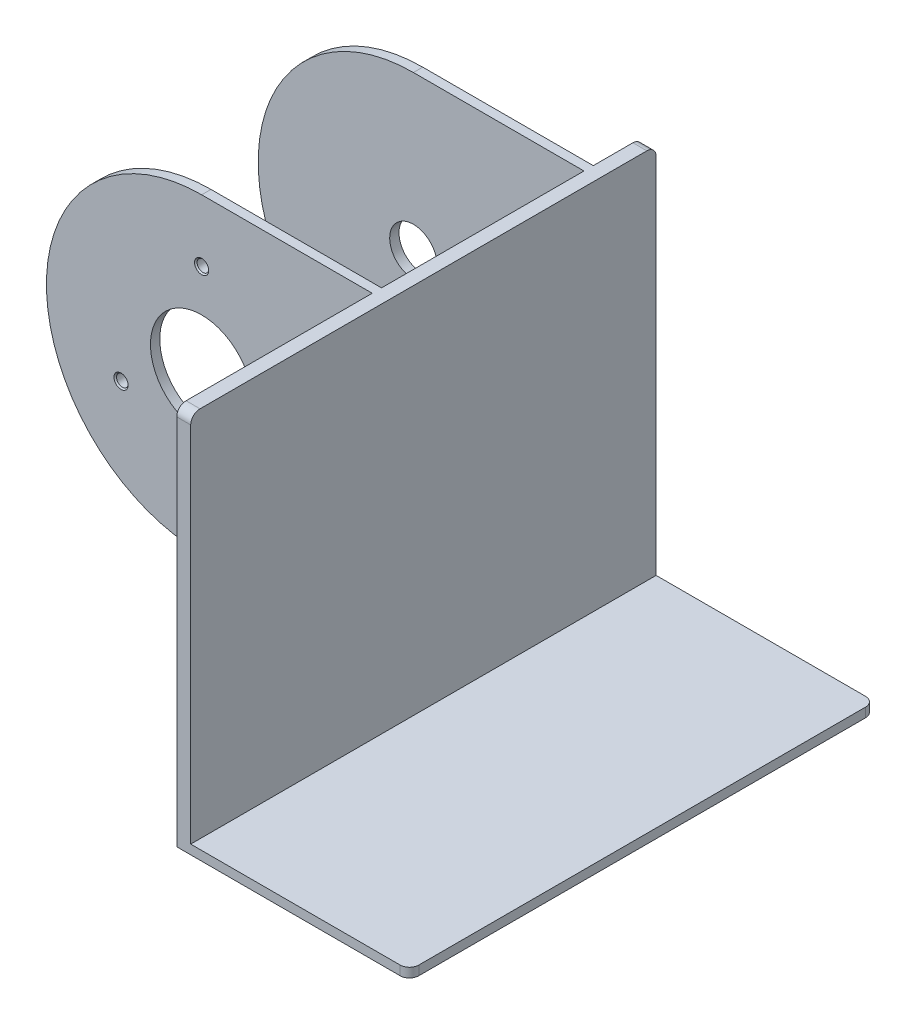
SolidWorks part; units mm, degrees
material "ABS"
ref_plane "前视基准面" through (0, 0, 0) normal (0, 0, 1) x (1, 0, 0)
ref_plane "上视基准面" through (0, 0, 0) normal (0, 1, 0) x (1, 0, 0)
ref_plane "右视基准面" through (0, 0, 0) normal (1, 0, 0) x (0, 0, -1)
sketch "草图1" plane through (0, 0, 0) normal (0, 1, 0) x (1, 0, 0)
  line L1 (-25, -50) -> (25, -50)
  line L2 (-25, -50) -> (-25, 50)
  line L3 (-25, 50) -> (25, 50)
  line L4 (25, -50) -> (25, 50)
  line L5 (-25, -50) -> (25, 50) construction
  line L6 (-25, 50) -> (25, -50) construction
  point P0 (0, 0)
  dimension "D1" = 100
  dimension "D2" = 50
extrude "凸台-拉伸1" add sketch "草图1" along normal blind 2
sketch "草图2" plane through (0, 2, 0) normal (0, 1, 0) x (1, 0, 0)
  line L0 (-25, -50) -> (25, -50) construction
  line L1 (-25, 50) -> (-22, 50)
  line L2 (-25, 50) -> (-25, -50)
  line L3 (-25, -50) -> (-22, -50)
  line L4 (-22, 50) -> (-22, -50)
  dimension "D1" = 3
extrude "凸台-拉伸2" add sketch "草图2" along normal blind 80
sketch "草图3" plane through (-25, 0, 0) normal (-1, 0, 0) x (0, 0, 1)
  line L1 (-50, 82) -> (-48, 82)
  line L2 (-50, 82) -> (-50, 15.3)
  line L3 (-50, 15.3) -> (-48, 15.3)
  line L4 (-48, 82) -> (-48, 15.3)
  dimension "D1" = 66.7
  dimension "D2" = 2
extrude "凸台-拉伸3" add sketch "草图3" along normal blind 70 contours L4 L3 L2 L1
sketch "草图4" plane through (0, 0, -50) normal (0, 0, -1) x (-1, 0, 0)
  line L2 (61.65, 82) -> (95, 82)
  line L3 (95, 82) -> (95, 48.65)
  line L4 (61.65, 15.3) -> (95, 15.3)
  line L5 (95, 15.3) -> (95, 48.65)
  line L6 (22, 82) -> (95, 82) construction
  arc A1 (61.65, 82) -> (95, 48.65) centre (61.65, 48.65) cw
  arc A2 (95, 48.65) -> (61.65, 15.3) centre (61.65, 48.65) cw
  point P17 (95, 48.65)
  line M4 (95, 15.3) -> (95, 82)
  line M5 (95, 82) -> (22, 82)
  dimension "D1" = 33.35
extrude "切除-拉伸4" cut sketch "草图4" against normal up to next contours A1 M5 M4 | A2 L4 L5
sketch "草图8" plane through (-25, 0, 0) normal (-1, 0, 0) x (0, 0, 1)
  line L0 (-48, 82) -> (50, 82) construction
  line L1 (6, 82) -> (8, 82)
  line L2 (6, 82) -> (6, 15.3)
  line L3 (6, 15.3) -> (8, 15.3)
  line L4 (8, 82) -> (8, 15.3)
  line L5 (50, 82) -> (50, 0) construction
  dimension "D1" = 42
  dimension "D2" = 66.7
  dimension "D3" = 2
extrude "凸台-拉伸4" add sketch "草图8" along normal blind 70 contours L2 L3 L4 L1
sketch "草图9" plane through (0, 0, 8) normal (0, 0, 1) x (1, 0, 0)
  line L0 (-61.65, 82) -> (-95, 82)
  line L1 (-95, 48.65) -> (-95, 15.3)
  line L4 (-25, 15.3) -> (-25, 82)
  line L5 (-25, 82) -> (-95, 82)
  line L6 (-95, 82) -> (-95, 15.3)
  line L7 (-95, 15.3) -> (-25, 15.3)
  line L8 (-25, 15.3) -> (-25, 82)
  line L9 (-25, 82) -> (-95, 82)
  line L10 (-95, 82) -> (-95, 15.3)
  line L11 (-95, 15.3) -> (-25, 15.3)
  arc A0 (-61.65, 82) -> (-61.65, 15.3) centre (-61.65, 48.65) ccw construction
  arc A1 (-61.65, 82) -> (-61.65, 15.3) centre (-61.65, 48.65) ccw
  dimension "D1" = 0
extrude "切除-拉伸5" cut sketch "草图9" against normal up to next contours L0 A1
sketch "草图10" plane through (0, 0, 8) normal (0, 0, 1) x (1, 0, 0)
  line L0 (-61.65, 48.65) -> (-61.65, 68.65) construction
  line L1 (-61.65, 48.65) -> (-44.3295, 38.65) construction
  line L2 (-61.65, 48.65) -> (-78.9705, 38.65) construction
  circle A0 centre (-61.65, 48.65) radius 20 construction
  point P7 (-61.65, 68.65)
  point P8 (-44.3295, 38.65)
  point P9 (-78.9705, 38.65)
  dimension "D1" = 40
  dimension "D2" = 120
  dimension "D3" = 120
hole_wizard "M3 螺纹孔1" positions "草图10" profile "草图11" tap size "M3" standard "GB"
sketch "草图11" plane through (-78.9705, 38.65, 8) normal (1, 0, 0) x (0, -1, 0)
  line L0 (0, 0) -> (0, 2)
  line L1 (0, 2) -> (1.25, 2)
  line L2 (1.25, 2) -> (1.25, 0.275)
  line L3 (1.25, 0.275) -> (1.525, 0)
  line L5 (1.525, 0) -> (0, 0)
  line L6 (-1.25, 0.275) -> (-1.525, 0) construction
  line L11 (0, -6.35) -> (0, 107.95) construction
  dimension "通孔螺纹孔钻头直径" = 2.5
  dimension "通孔螺纹孔钻头深度" = 2
  dimension "近端锥形沉头孔直径" = 3.05
  dimension "近端锥形沉头孔角度" = 90
cosmetic thread "孔螺纹线5" parameters "D2"=3
cosmetic thread "孔螺纹线6" parameters "D2"=3
cosmetic thread "孔螺纹线7" parameters "D2"=3
fillet "圆角1" radius 2 3 edges at (-23.5, 82, 50) (25, 1, -50) (25, 1, 50)
sketch "草图12" plane through (0, 0, 8) normal (0, 0, 1) x (1, 0, 0)
  circle A0 centre (-61.65, 48.65) radius 11
  dimension "D1" = 22
extrude "切除-拉伸6" cut sketch "草图12" against normal up to next
sketch "草图13" plane through (0, 0, -50) normal (0, 0, -1) x (-1, 0, 0)
  circle A0 centre (61.65, 48.65) radius 14.5
  dimension "D1" = 29
extrude "切除-拉伸7" cut sketch "草图13" against normal up to next
sketch "草图14" plane through (-25, 0, 0) normal (-1, 0, 0) x (0, 0, 1)
  line L0 (-48, 82) -> (6, 82) construction
  line L1 (-39.5, 82) -> (-37.5, 82)
  line L2 (-39.5, 82) -> (-39.5, 15.3)
  line L3 (-39.5, 15.3) -> (-37.5, 15.3)
  line L4 (-37.5, 82) -> (-37.5, 15.3)
  line L5 (-50, 82) -> (-50, 15.3) construction
  dimension "D1" = 2
  dimension "D2" = 10.5
  dimension "D3" = 66.7
extrude "凸台-拉伸5" add sketch "草图14" along normal blind 70
sketch "草图15" plane through (0, 0, -39.5) normal (0, 0, -1) x (-1, 0, 0)
  line L0 (95, 82) -> (95, 15.3) construction
  line L1 (61.65, 15.3) -> (25, 15.3) construction
  circle A0 centre (61.65, 48.65) radius 5.1
  dimension "D1" = 10.2
  dimension "D2" = 33.35
  dimension "D3" = 33.35
extrude "切除-拉伸8" cut sketch "草图15" against normal up to next
sketch "草图18" plane through (0, 0, -39.5) normal (0, 0, -1) x (-1, 0, 0)
  line L0 (95, 82) -> (95, 15.3)
  line L1 (95, 15.3) -> (58.4851, 15.3)
  line L2 (95, 82) -> (58.4269, 82)
  arc A0 (61.65, 82) -> (95, 48.65) centre (61.65, 48.65) cw
  arc A1 (61.65, 15.3) -> (95, 48.65) centre (61.65, 48.65) ccw
  line M6 (95, 15.3) -> (95, 82)
  line M7 (95, 82) -> (25, 82)
  dimension "D1" = 33.35
  dimension "D2" = 33.35
extrude "切除-拉伸9" cut sketch "草图18" against normal through all and the other way through all contours A1 L1 M6 | A0 L0 M7
sketch "草图19" plane through (-25, 0, 0) normal (-1, 0, 0) x (0, 0, 1)
  line L1 (-50, 82) -> (-48, 82)
  line L2 (-50, 82) -> (-50, 15.3)
  line L3 (-50, 15.3) -> (-48, 15.3)
  line L4 (-48, 82) -> (-48, 15.3)
  dimension "D1" = 2
  dimension "D2" = 66.7
extrude "切除-拉伸10" cut sketch "草图19" along normal through all
fillet "圆角2" radius 2 1 edges at (-23.5, 82, -50)
